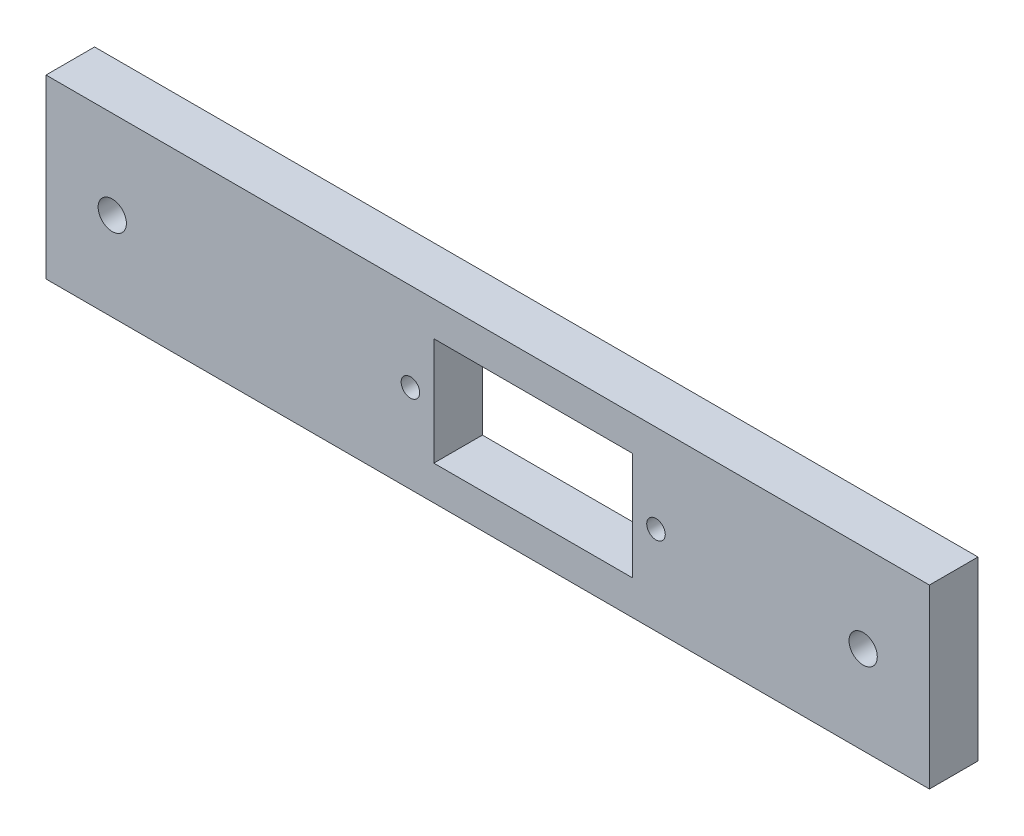
SolidWorks part; units mm, degrees
material "ﾁｰｸ材"
ref_plane "正面" through (0, 0, 0) normal (0, 0, 1) x (1, 0, 0)
ref_plane "平面" through (0, 0, 0) normal (0, 1, 0) x (1, 0, 0)
ref_plane "右側面" through (0, 0, 0) normal (1, 0, 0) x (0, 0, -1)
sketch "ｽｹｯﾁ1" plane through (0, 0, 0) normal (0, 0, 1) x (1, 0, 0)
  line L1 (-50, 10) -> (50, 10)
  line L2 (-50, 10) -> (-50, -10)
  line L3 (-50, -10) -> (50, -10)
  line L4 (50, 10) -> (50, -10)
  line L5 (-50, 10) -> (50, -10) construction
  line L6 (-50, -10) -> (50, 10) construction
  point P0 (0, 0)
  dimension "D1" = 20
  dimension "D2" = 100
extrude "ﾎﾞｽ - 押し出し1" add sketch "ｽｹｯﾁ1" along normal blind 5.5
sketch "ｽｹｯﾁ2" plane through (0, 0, 5.5) normal (0, 0, 1) x (1, 0, 0)
  line L0 (-50, 10) -> (-50, -10) construction
  line L1 (-6.1, 6.1) -> (16.4, 6.1)
  line L2 (-6.1, 6.1) -> (-6.1, -6.1)
  line L3 (-6.1, -6.1) -> (16.4, -6.1)
  line L4 (16.4, 6.1) -> (16.4, -6.1)
  line L5 (-6.1, 6.1) -> (16.4, -6.1) construction
  line L6 (-6.1, -6.1) -> (16.4, 6.1) construction
  line L7 (50, -10) -> (50, 10) construction
  circle A0 centre (-42.5, 0) radius 1.6
  circle A1 centre (42.5, 0) radius 1.6
  circle A2 centre (-8.75, 0) radius 1.05
  circle A3 centre (19.05, 0) radius 1.05
  point P0 (5.15, 0)
  dimension "D4" = 3.2
  dimension "D7" = 3.2
  dimension "D8" = 2.65
  dimension "D9" = 2.1
  dimension "D1" = 12.2
  dimension "D2" = 22.5
  dimension "D3" = 6.1
  dimension "D5" = 7.5
  dimension "D6" = 7.5
  dimension "D10" = 2.65
extrude "ｶｯﾄ - 押し出し1" cut sketch "ｽｹｯﾁ2" against normal through all
